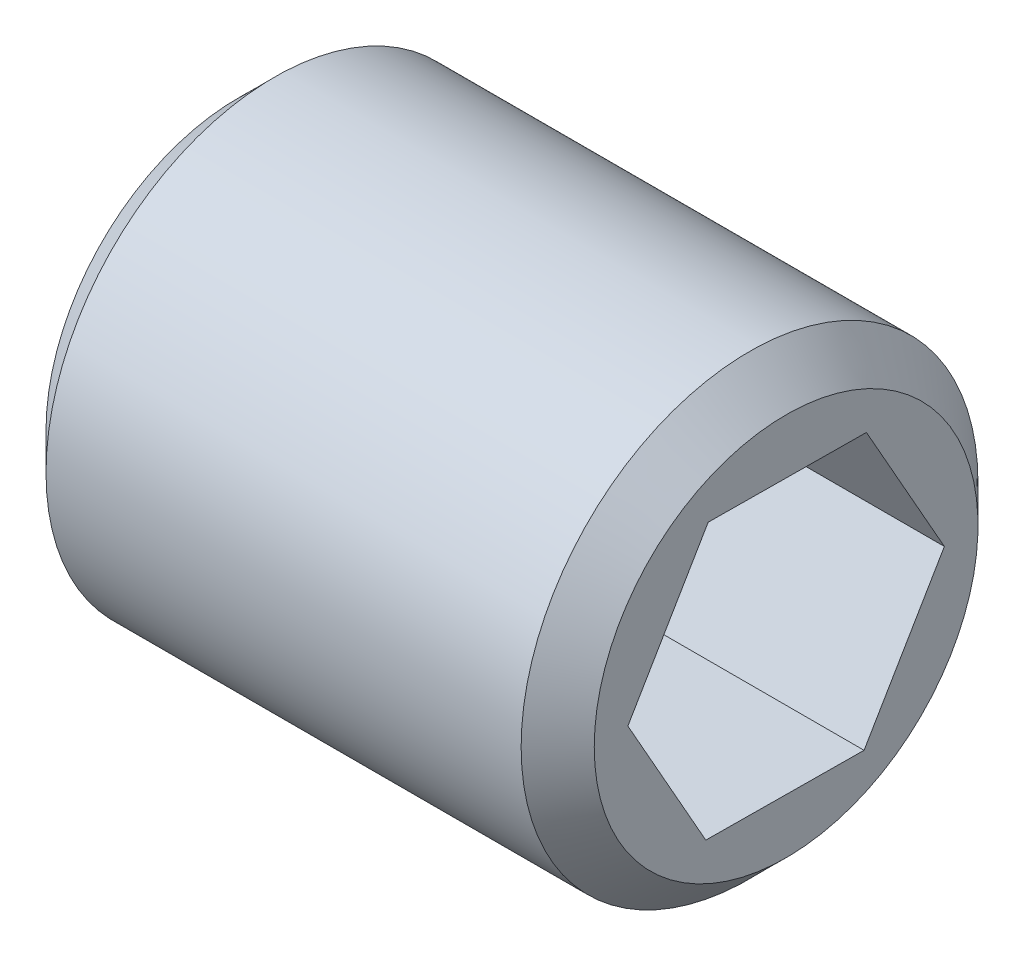
SolidWorks part; units mm, degrees
material "0.6010 (EN-GJL-100)"
ref_plane "Plan de face" through (0, 0, 0) normal (0, 0, 1) x (1, 0, 0)
ref_plane "Plan de dessus" through (0, 0, 0) normal (0, 1, 0) x (1, 0, 0)
ref_plane "Plan de droite" through (0, 0, 0) normal (1, 0, 0) x (0, 0, -1)
sketch "Esquisse1" plane through (0, 0, 0) normal (0, 0, 1) x (1, 0, 0)
  line L0 (-47.1276, 0) -> (50.3288, 0) construction
  line L1 (-3, 0) -> (-3, 1.05)
  line L2 (-3, 1.05) -> (-2.8, 1.25)
  line L3 (-2.8, 1.25) -> (-0.2, 1.25)
  line L4 (-0.2, 1.25) -> (0, 1.05)
  line L5 (0, 1.05) -> (0, 0)
  line L6 (-3, 0) -> (0, 0)
  dimension "D1" = 3
  dimension "D2" = 0.2
  dimension "D3" = 0.2
  dimension "D4" = 0.2
  dimension "D5" = 0.2
  dimension "D6" = 1.25
revolve "Révolution1" add sketch "Esquisse1" angle 360 about L0
sketch "Esquisse2" plane through (0, 0, 0) normal (1, 0, 0) x (0, 0, -1)
  line L1 (0.4394, 0.7462) -> (-0.4265, 0.7537)
  line L2 (-0.4265, 0.7537) -> (-0.866, 0.0074)
  line L3 (-0.866, 0.0074) -> (-0.4394, -0.7462)
  line L4 (-0.4394, -0.7462) -> (0.4265, -0.7537)
  line L5 (0.4265, -0.7537) -> (0.866, -0.0074)
  line L6 (0.866, -0.0074) -> (0.4394, 0.7462)
  circle A0 centre (0, 0) radius 0.75 construction
  dimension "D1" = 1.5
  dimension "D2" = 0.4394
extrude "Enlèv. mat.-Extru.1" cut sketch "Esquisse2" against normal blind 1.5
